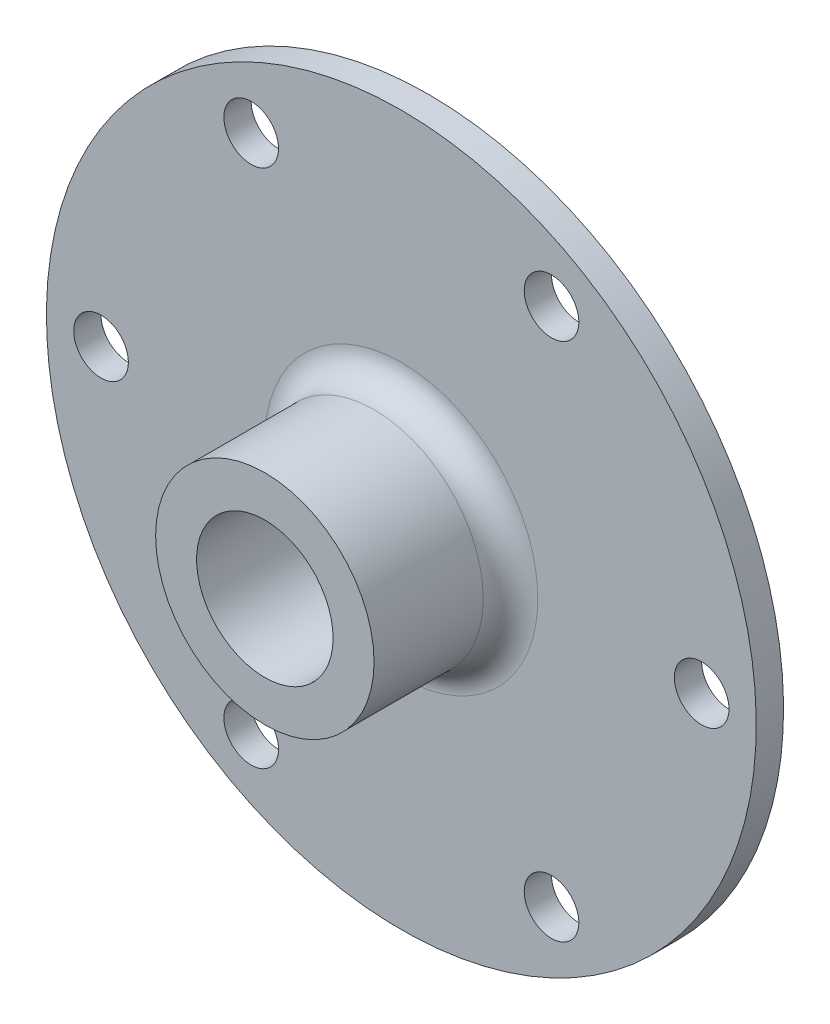
SolidWorks part; units mm, degrees
material "AISI 1020"
ref_plane "Front Plane" through (0, 0, 0) normal (0, 0, 1) x (1, 0, 0)
ref_plane "Top Plane" through (0, 0, 0) normal (0, 1, 0) x (1, 0, 0)
ref_plane "Right Plane" through (0, 0, 0) normal (1, 0, 0) x (0, 0, -1)
sketch "Sketch1" plane through (0, 0, 0) normal (1, 0, 0) x (0, 0, -1)
  line L2 (0, 0) -> (0, 41.275)
  line L3 (0, 41.275) -> (-3.175, 41.275)
  line L4 (-3.175, 12.7) -> (-3.175, 41.275)
  line L5 (0, 0) -> (-19.05, 0)
  line L7 (-3.175, 12.7) -> (-19.05, 12.7)
  line L8 (-19.05, 0) -> (-19.05, 12.7)
  dimension "D1" = 3.175
  dimension "D2" = 12.7
  dimension "D3" = 41.275
  dimension "D4" = 19.05
revolve "Flange Base" add sketch "Sketch1" angle 360 about L5
sketch "Sketch2" plane through (0, 0, 19.05) normal (0, 0, 1) x (1, 0, 0)
  circle A0 centre (0, 0) radius 7.9375
  dimension "D1" = 15.875
extrude "Cut-Extrude1" cut sketch "Sketch2" against normal through all
sketch "Sketch3" plane through (0, 0, 3.175) normal (0, 0, 1) x (1, 0, 0)
  line L0 (0, 0) -> (34.925, 0) construction
  circle A0 centre (34.925, 0) radius 3.175
  dimension "D2" = 6.35
  dimension "D1" = 34.925
extrude "Cut-Extrude2" cut sketch "Sketch3" against normal through all
pattern_circular "CirPattern4" count 6 over 360 about axis through (0, 0, 0) along (0, 0, 1) of "Cut-Extrude2"
fillet "Fillet1" radius 3.175 1 edges at (0, 12.7, 3.175)
